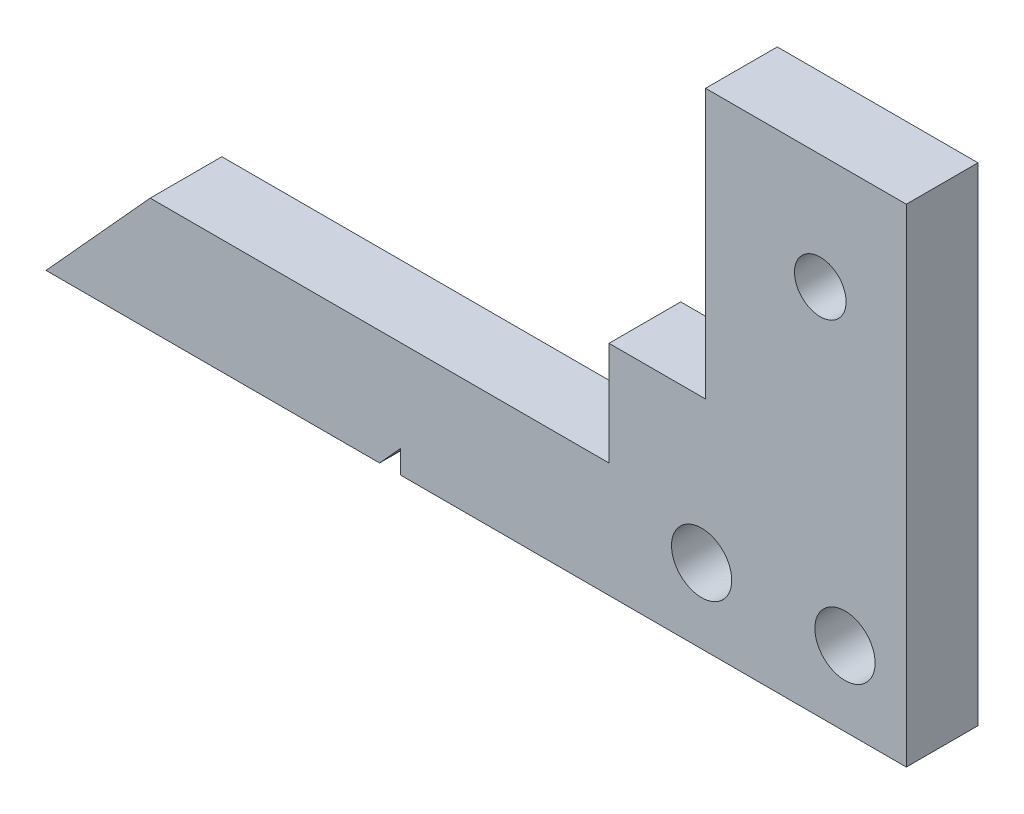
SolidWorks part; units mm, degrees
ref_plane "Front Plane" through (0, 0, 0) normal (0, 0, 1) x (1, 0, 0)
ref_plane "Top Plane" through (0, 0, 0) normal (0, 1, 0) x (1, 0, 0)
ref_plane "Right Plane" through (0, 0, 0) normal (1, 0, 0) x (0, 0, -1)
sketch "Sketch1" plane through (0, 0, 0) normal (0, 0, 1) x (1, 0, 0)
  line L20 (0, 0) -> (4.6137, 5.08)
  line L21 (4.6137, 5.08) -> (24.9337, 5.08)
  line L22 (24.9337, 5.08) -> (24.9337, 9.6718)
  line L23 (24.9337, 9.6718) -> (29.21, 9.6718)
  line L24 (29.21, 9.6718) -> (29.21, 21.59)
  line L25 (29.21, 21.59) -> (38.1, 21.59)
  line L26 (38.1, 21.59) -> (38.1, 0)
  line L27 (0, 0) -> (14.7737, 0)
  line L28 (14.7737, 0) -> (15.7006, 1.0206)
  line L29 (15.7006, 1.0206) -> (15.7006, 0)
  line L30 (15.7006, 0) -> (38.1, 0)
  circle A0 centre (29.034, 3.2995) radius 1.3335
  circle A1 centre (35.384, 3.2995) radius 1.3335
  circle A2 centre (34.29, 16.51) radius 1.143
  dimension "D5" = 2.667
  dimension "D7" = 2.286
  dimension "D8" = 5.08
  dimension "D9" = 3.81
  dimension "D1" = 20.32
  dimension "D2" = 38.1
  dimension "D3" = 21.59
  dimension "D4" = 5.08
  dimension "D6" = 6.35
  dimension "D10" = 8.89
extrude "Boss-Extrude1" add sketch "Sketch1" along normal blind 3.175
